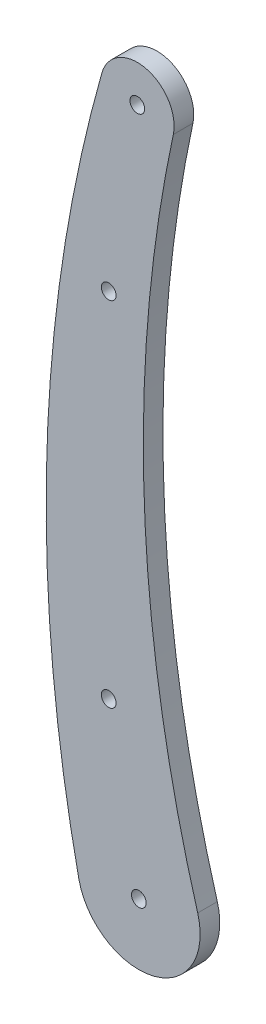
SolidWorks part; units mm, degrees
material "Acrílico (Impacto medio-alto)"
ref_plane "Piano frontale" through (0, 0, 0) normal (0, 0, 1) x (1, 0, 0)
ref_plane "Piano superiore" through (0, 0, 0) normal (0, 1, 0) x (1, 0, 0)
ref_plane "Piano destro" through (0, 0, 0) normal (1, 0, 0) x (0, 0, -1)
sketch "Schizzo1" plane through (0, 0, 0) normal (0, 0, 1) x (1, 0, 0)
  circle A0 centre (0, 0) radius 1.5
  circle A1 centre (-0.3094, 139.9997) radius 1.5
  arc A2 (7.024, 138.4277) -> (-7.5254, 142.0442) centre (-0.3094, 139.9997) ccw
  arc A3 (-12.2223, -2.6202) -> (11.9963, 3.5125) centre (0, 0) ccw
  arc A4 (-7.5254, 142.0442) -> (-12.2223, -2.6202) centre (281.1129, 60.2643) ccw
  arc A5 (7.024, 138.4277) -> (11.9963, 3.5125) centre (275.9157, 80.7886) ccw
  dimension "D1" = 3
  dimension "D2" = 3
  dimension "D4" = 15
  dimension "D5" = 25
  dimension "D6" = 600
  dimension "D7" = 550
  dimension "D3" = 140
extrude "Estrusione-Estrusione1" add sketch "Schizzo1" along normal blind 4
sketch "Schizzo2" plane through (0, 0, 4) normal (0, 0, 1) x (1, 0, 0)
  circle A0 centre (-6.1421, 104.1667) radius 1.5
  circle A1 centre (-6.1421, 32.2137) radius 1.5
  dimension "D1" = 3
  dimension "D2" = 3
extrude "Taglio-Estrusione1" cut sketch "Schizzo2" against normal blind 25
